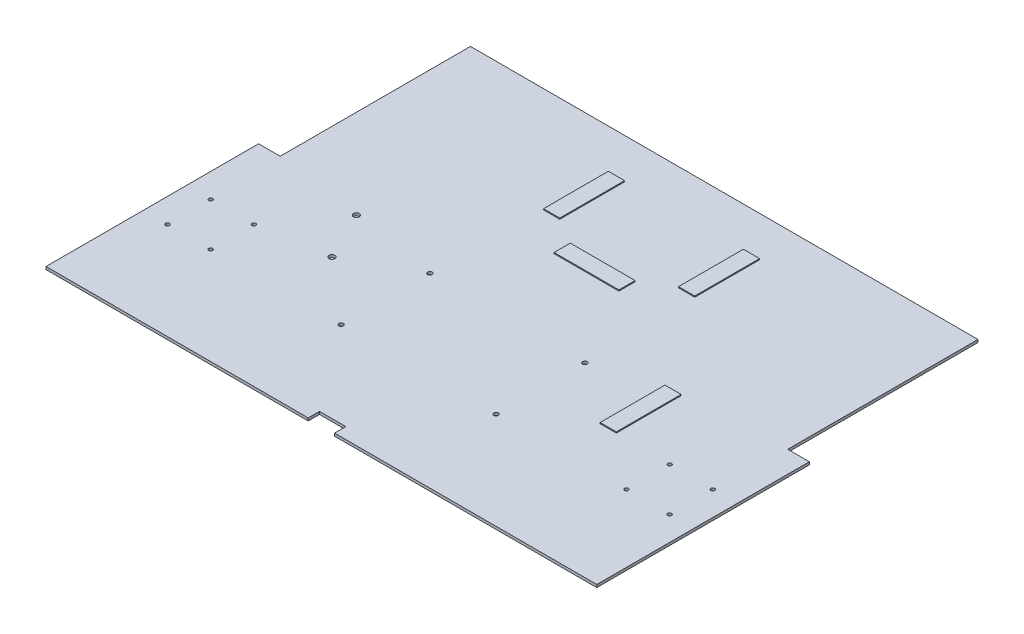
SolidWorks part; units mm, degrees
ref_plane "Front Plane" through (0, 0, 0) normal (0, 0, 1) x (1, 0, 0)
ref_plane "Top Plane" through (0, 0, 0) normal (0, 1, 0) x (1, 0, 0)
ref_plane "Right Plane" through (0, 0, 0) normal (1, 0, 0) x (0, 0, -1)
sketch "Sketch1" plane through (0, 0, 0) normal (0, 1, 0) x (1, 0, 0)
  line L0 (-298.45, 13.1242) -> (-298.45, 236.855)
  line L1 (-323.85, -236.855) -> (323.85, -236.855)
  line L2 (-323.85, -236.855) -> (-323.85, 13.1242)
  line L3 (298.45, 13.1242) -> (298.45, 236.855)
  line L4 (323.85, 13.1242) -> (323.85, -236.855)
  line L5 (0, -236.855) -> (0, 236.855) construction
  line L6 (244.475, -71.755) -> (244.475, -122.555) construction
  line L7 (-323.85, 13.1242) -> (-298.45, 13.1242)
  line L8 (-91.1352, -122.555) -> (91.1352, -122.555) construction
  line L9 (323.85, 13.1242) -> (298.45, 13.1242)
  line L10 (-298.45, 236.855) -> (298.45, 236.855)
  line L15 (-91.1352, -122.555) -> (-91.1352, -18.161) construction
  line L16 (-91.1352, -18.161) -> (91.1352, -18.161) construction
  line L17 (91.1352, -122.555) -> (91.1352, -18.161) construction
  line L18 (-91.1352, -122.555) -> (91.1352, -18.161) construction
  line L19 (-91.1352, -18.161) -> (91.1352, -122.555) construction
  line L20 (-295.275, -71.755) -> (-244.475, -71.755) construction
  line L21 (-295.275, -71.755) -> (-295.275, -122.555) construction
  line L22 (-295.275, -122.555) -> (-244.475, -122.555) construction
  line L23 (-244.475, -71.755) -> (-244.475, -122.555) construction
  line L24 (295.275, -122.555) -> (244.475, -122.555) construction
  line L25 (295.275, -71.755) -> (295.275, -122.555) construction
  line L26 (295.275, -71.755) -> (244.475, -71.755) construction
  line L27 (-193.675, -2.0423) -> (-193.675, -59.055) construction
  line L28 (-193.675, -59.055) -> (-165.4558, -59.055) construction
  circle A0 centre (91.1352, -18.161) radius 2.667
  circle A1 centre (91.1352, -122.555) radius 2.667
  circle A2 centre (-91.1352, -122.555) radius 2.667
  circle A3 centre (-91.1352, -18.161) radius 2.667
  circle A4 centre (-295.275, -71.755) radius 2.2479
  circle A5 centre (-244.475, -71.755) radius 2.2479
  circle A6 centre (-244.475, -122.555) radius 2.2479
  circle A7 centre (-295.275, -122.555) radius 2.2479
  circle A8 centre (295.275, -122.555) radius 2.2479
  circle A9 centre (244.475, -122.555) radius 2.2479
  circle A10 centre (244.475, -71.755) radius 2.2479
  circle A11 centre (295.275, -71.755) radius 2.2479
  circle A12 centre (-193.675, -2.0423) radius 3.429
  circle A13 centre (-165.4558, -59.055) radius 3.429
  point P5 (0, -70.358)
  point P6 (-323.85, 13.1242)
  dimension "D8" = 182.2704
  dimension "D6" = 5.334
  dimension "D9" = 4.4958
  dimension "D12" = 6.858
  dimension "D2" = 473.71
  dimension "D3" = 249.9792
  dimension "D4" = 114.3
  dimension "D5" = 25.4
  dimension "D7" = 104.394
  dimension "D10" = 50.8
  dimension "D11" = 50.8
  dimension "D13" = 57.0127
  dimension "D14" = 28.2192
  dimension "D15" = 647.7
  dimension "D16" = 28.575
  dimension "D17" = 114.3
  dimension "D18" = 130.175
  dimension "D19" = 28.575
  dimension "D20" = 114.3
  dimension "D21" = 177.8
extrude "Boss-Extrude1" add sketch "Sketch1" along normal mid plane 3.175
sketch "Sketch4" plane through (0, 1.5875, 0) normal (0, 1, 0) x (1, 0, 0)
  line L0 (-323.85, -236.855) -> (323.85, -236.855) construction
  line L1 (-15.4914, -250.0918) -> (15.4914, -250.0918)
  line L2 (-15.4914, -250.0918) -> (-15.4914, -223.6182)
  line L3 (-15.4914, -223.6182) -> (15.4914, -223.6182)
  line L4 (15.4914, -250.0918) -> (15.4914, -223.6182)
  line L5 (-15.4914, -250.0918) -> (15.4914, -223.6182) construction
  line L6 (-15.4914, -223.6182) -> (15.4914, -250.0918) construction
  point P0 (0, -236.855)
extrude "Cut-Extrude2" cut sketch "Sketch4" against normal through all
sketch "Sketch5" plane through (0, 1.5875, 0) normal (0, 1, 0) x (1, 0, 0)
  line L0 (0, -223.6182) -> (0, 236.855) construction
  line L1 (-88.9, 84.455) -> (88.9, 84.455) construction
  line L2 (-88.9, 84.455) -> (-88.9, 236.855) construction
  line L3 (88.9, 84.455) -> (88.9, 236.855) construction
  line L4 (298.45, 236.855) -> (-298.45, 236.855) construction
  line L5 (69.85, 189.5213) -> (88.9, 113.3213) construction
  line L6 (15.4914, -223.6182) -> (-15.4914, -223.6182) construction
  line L7 (69.85, 113.3213) -> (88.9, 189.5213) construction
  line L8 (-38.1, 74.93) -> (38.1, 74.93)
  line L9 (-38.1, 74.93) -> (-38.1, 93.98)
  line L10 (-38.1, 93.98) -> (38.1, 93.98)
  line L11 (38.1, 74.93) -> (38.1, 93.98)
  line L12 (-38.1, 74.93) -> (38.1, 93.98) construction
  line L13 (-38.1, 93.98) -> (38.1, 74.93) construction
  line L14 (-69.85, 113.3213) -> (-88.9, 113.3213)
  line L15 (-69.85, 113.3213) -> (-69.85, 189.5213)
  line L16 (-69.85, 189.5213) -> (-88.9, 189.5213)
  line L17 (-88.9, 113.3213) -> (-88.9, 189.5213)
  line L18 (-69.85, 113.3213) -> (-88.9, 189.5213) construction
  line L19 (-69.85, 189.5213) -> (-88.9, 113.3213) construction
  line L20 (88.9, 113.3213) -> (88.9, 189.5213)
  line L21 (69.85, 189.5213) -> (88.9, 189.5213)
  line L22 (69.85, 113.3213) -> (69.85, 189.5213)
  line L23 (69.85, 113.3213) -> (88.9, 113.3213)
  line L25 (162.0988, -71.153) -> (181.1488, -71.153)
  line L26 (162.0988, -71.153) -> (162.0988, 5.047)
  line L27 (162.0988, 5.047) -> (181.1488, 5.047)
  line L28 (181.1488, -71.153) -> (181.1488, 5.047)
  line L29 (162.0988, -71.153) -> (181.1488, 5.047) construction
  line L30 (162.0988, 5.047) -> (181.1488, -71.153) construction
  point P5 (0, 84.455)
  point P10 (0, 84.455)
  point P17 (-79.375, 151.4213)
  point P26 (79.375, 151.4213)
  point P27 (171.6238, -33.053)
  dimension "D1" = 177.8
  dimension "D2" = 152.4
  dimension "D3" = 19.05
  dimension "D4" = 76.2
  dimension "D5" = 76.2
  dimension "D6" = 19.05
  dimension "D7" = 19.05
  dimension "D8" = 76.2
extrude "Boss-Extrude2" add sketch "Sketch5" along normal blind 1.27
